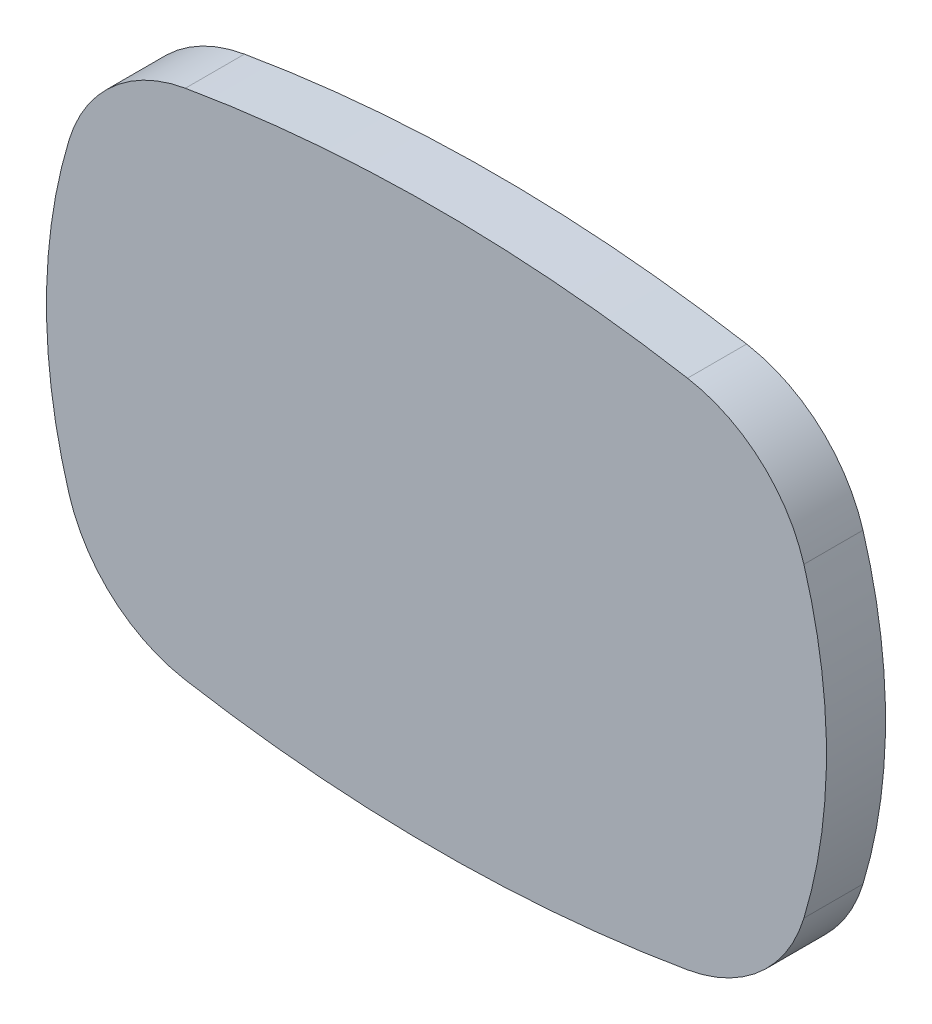
SolidWorks part; units mm, degrees
ref_plane "前基準面" through (0, 0, 0) normal (0, 0, 1) x (1, 0, 0)
ref_plane "上基準面" through (0, 0, 0) normal (0, 1, 0) x (1, 0, 0)
ref_plane "右基準面" through (0, 0, 0) normal (1, 0, 0) x (0, 0, -1)
sketch "草圖1" plane through (0, 0, 0) normal (0, 0, 1) x (1, 0, 0)
  line L0 (24, 32) -> (-24, 32) construction
  arc A0 (62.1843, 57.9282) -> (42.4936, 75.3621) centre (38.2442, 50.7259) ccw
  arc A1 (62.1843, 57.9282) -> (62.1843, 6.0718) centre (-24, 32) cw
  arc A2 (62.1843, 6.0718) -> (42.4936, -11.3621) centre (38.2442, 13.2741) cw
  arc A3 (42.4936, -11.3621) -> (-42.4936, -11.3621) centre (0, 235) cw
  arc A4 (-42.4936, -11.3621) -> (-62.1843, 6.0718) centre (-38.2442, 13.2741) cw
  arc A5 (-62.1843, 6.0718) -> (-62.1843, 57.9282) centre (24, 32) cw
  arc A6 (-62.1843, 57.9282) -> (-42.4936, 75.3621) centre (-38.2442, 50.7259) cw
  arc A7 (-42.4936, 75.3621) -> (42.4936, 75.3621) centre (0, -171) cw
  point P15 (0, 32)
  point P18 (66, 32)
  point P19 (-66, 32)
  point P22 (0, 79)
  point P23 (0, -15)
  dimension "D1" = 25
  dimension "D2" = 90
  dimension "D3" = 25
  dimension "D4" = 250
  dimension "D5" = 25
  dimension "D6" = 90
  dimension "D7" = 25
  dimension "D8" = 250
  dimension "D9" = 132
  dimension "D10" = 94
  dimension "D11" = 32
extrude "填料-伸長1" add sketch "草圖1" along normal blind 10
